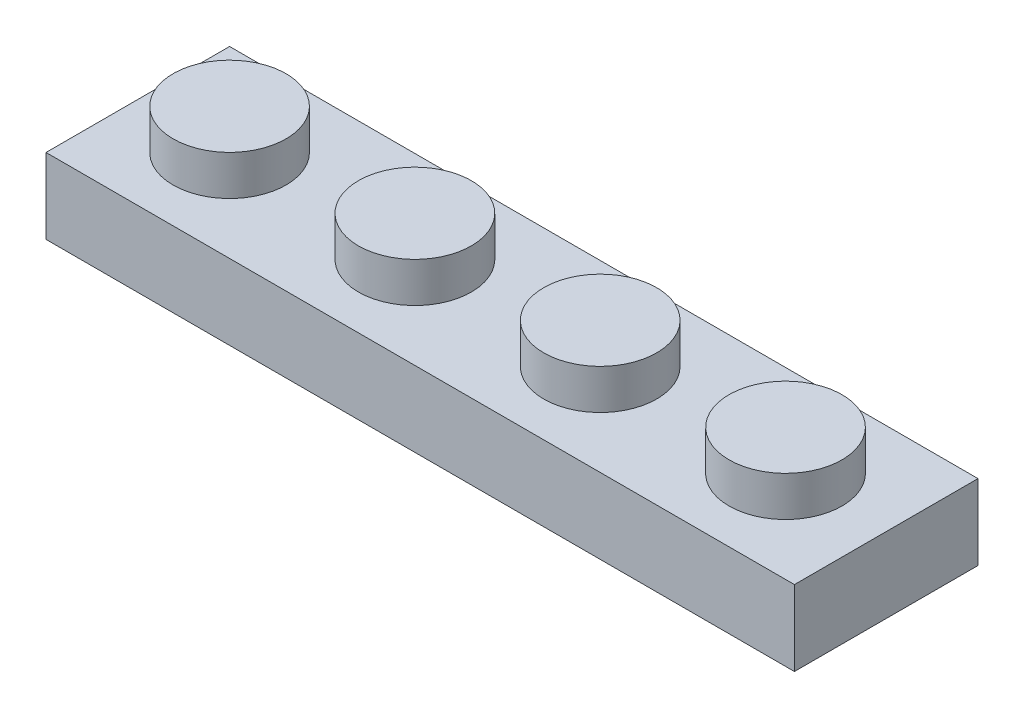
SolidWorks part; units mm, degrees
ref_plane "Спереди" through (0, 0, 0) normal (0, 0, 1) x (1, 0, 0)
ref_plane "Сверху" through (0, 0, 0) normal (0, 1, 0) x (1, 0, 0)
ref_plane "Справа" through (0, 0, 0) normal (1, 0, 0) x (0, 0, -1)
sketch "Эскиз1" plane through (0, 0, 0) normal (0, 1, 0) x (1, 0, 0)
  line L1 (15.9, -3.9) -> (-15.9, -3.9)
  line L2 (15.9, -3.9) -> (15.9, 3.9)
  line L3 (15.9, 3.9) -> (-15.9, 3.9)
  line L4 (-15.9, -3.9) -> (-15.9, 3.9)
  line L5 (15.9, -3.9) -> (-15.9, 3.9) construction
  line L6 (15.9, 3.9) -> (-15.9, -3.9) construction
  point P0 (0, 0)
  dimension "D1" = 31.8
  dimension "D2" = 7.8
extrude "Бобышка-Вытянуть1" add sketch "Эскиз1" along normal blind 3.2
sketch "Эскиз2" plane through (0, 3.2, 0) normal (0, 1, 0) x (1, 0, 0)
  line L0 (-15.9, 3.9) -> (-15.9, -3.9) construction
  line L1 (-15.9, -3.9) -> (15.9, -3.9) construction
  circle A0 centre (-12, 0) radius 2.4
  circle A1 centre (-4.126, 0) radius 2.4
  circle A2 centre (3.748, 0) radius 2.4
  circle A3 centre (11.622, 0) radius 2.4
  dimension "D1" = 3.9
  dimension "D2" = 3.9
  dimension "D3" = 4
extrude "Бобышка-Вытянуть2" add sketch "Эскиз2" along normal blind 1.7
sketch "Эскиз3" plane through (0, 0, 0) normal (0, -1, 0) x (1, 0, 0)
  line L0 (-15.9, -3.9) -> (-15.9, 3.9) construction
  line L1 (15.9, -3.9) -> (-15.9, -3.9) construction
  circle A0 centre (-12, 0) radius 2.5
  circle A1 centre (-4.126, 0) radius 2.5
  circle A2 centre (3.748, 0) radius 2.5
  circle A3 centre (11.622, 0) radius 2.5
  dimension "D1" = 3.9
  dimension "D2" = 3.9
  dimension "D3" = 4
extrude "Вырез-Вытянуть1" cut sketch "Эскиз3" against normal blind 1.8
